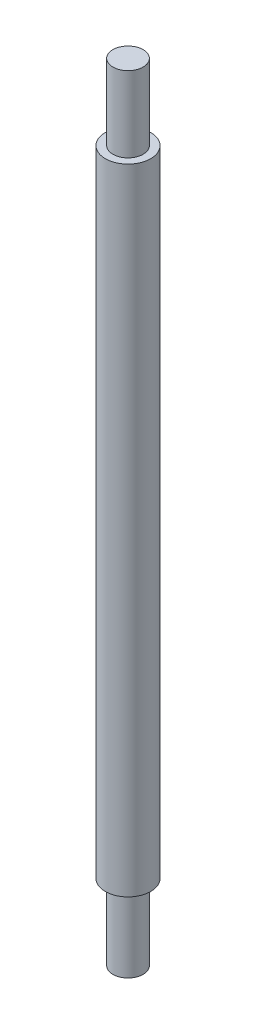
SolidWorks part; units mm, degrees
ref_plane "Front Plane" through (0, 0, 0) normal (0, 0, 1) x (1, 0, 0)
ref_plane "Top Plane" through (0, 0, 0) normal (0, 1, 0) x (1, 0, 0)
ref_plane "Right Plane" through (0, 0, 0) normal (1, 0, 0) x (0, 0, -1)
sketch "Sketch1" plane through (0, 0, 0) normal (0, 1, 0) x (1, 0, 0)
  circle A0 centre (0, 0) radius 3
  dimension "D1" = 6
extrude "Boss-Extrude1" add sketch "Sketch1" along normal mid plane 84
sketch "Sketch2" plane through (0, 42, 0) normal (0, 1, 0) x (1, 0, 0)
  circle A0 centre (0, 0) radius 2
  dimension "D1" = 4
extrude "Boss-Extrude2" add sketch "Sketch2" along normal blind 10
sketch "Sketch3" plane through (0, -42, 0) normal (0, -1, 0) x (1, 0, 0)
  circle A0 centre (0, 0) radius 2
  dimension "D1" = 4
extrude "Boss-Extrude3" add sketch "Sketch3" along normal blind 10
